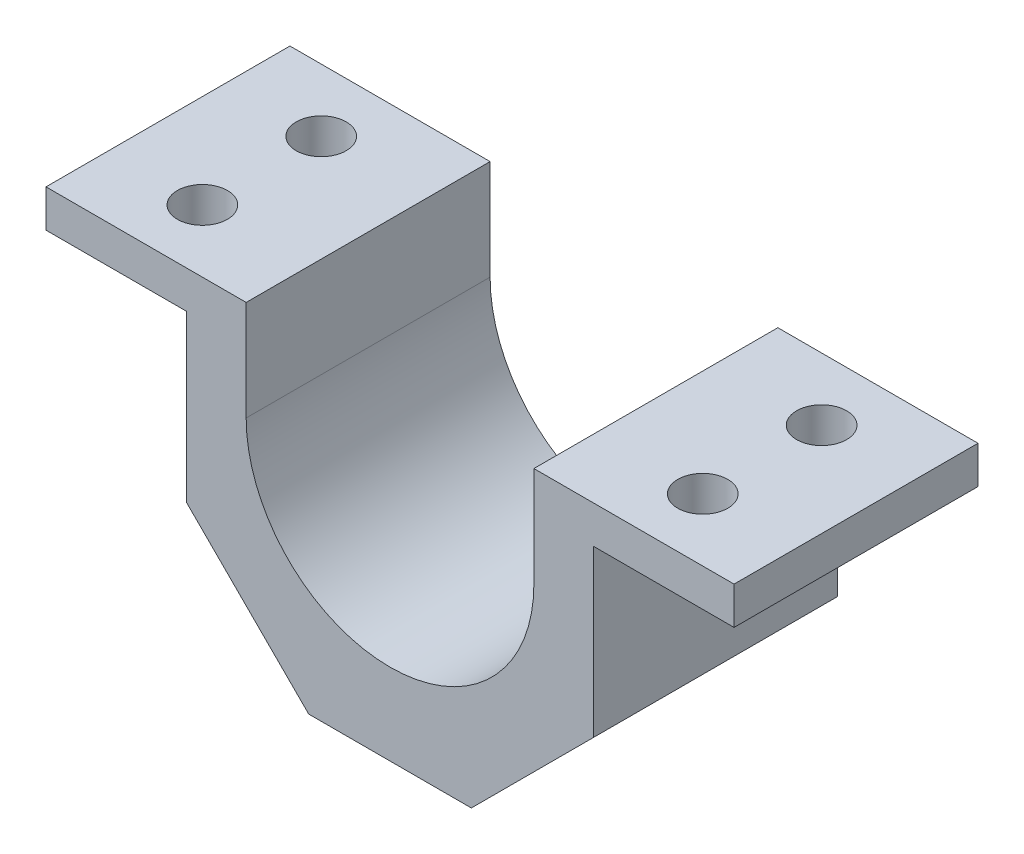
SolidWorks part; units mm, degrees
ref_plane "Front Plane" through (0, 0, 0) normal (0, 0, 1) x (1, 0, 0)
ref_plane "Top Plane" through (0, 0, 0) normal (0, 1, 0) x (1, 0, 0)
ref_plane "Right Plane" through (0, 0, 0) normal (1, 0, 0) x (0, 0, -1)
sketch "Sketch1" plane through (0, 0, 0) normal (0, 0, 1) x (1, 0, 0)
  line L0 (-55, 16) -> (-23, 16)
  line L1 (-23, 16) -> (-23, 0)
  line L2 (-55, 16) -> (-55, 10)
  line L3 (-55, 10) -> (-32.5, 10)
  line L4 (-32.5, 10) -> (-32.5, -36)
  line L5 (-32.5, -36) -> (32.5, -36)
  line L6 (32.5, -36) -> (32.5, 10)
  line L7 (32.5, 10) -> (55, 10)
  line L8 (55, 10) -> (55, 16)
  line L9 (55, 16) -> (23, 16)
  line L10 (23, 16) -> (23, 0)
  line L11 (0, 16.7921) -> (0, -7.6727) construction
  line L12 (32.5, -16.5) -> (13, -36)
  line L13 (-32.5, -16.5) -> (-13, -36)
  arc A0 (-23, 0) -> (23, 0) centre (0, 0) ccw
  point P18 (-55, 13)
  dimension "D1" = 23
  dimension "D2" = 65
  dimension "D3" = 16
  dimension "D4" = 6
  dimension "D5" = 52
  dimension "D6" = 110
  dimension "D7" = 45
  dimension "D8" = 13
extrude "Boss-Extrude2" add sketch "Sketch1" along normal mid plane 39 contours A0 L1 L0 L2 L3 L4 L13 L5 L12 L6 L7 L8 L9 L10
sketch "Sketch3" plane through (0, 16, 0) normal (0, 1, 0) x (1, 0, 0)
  line L0 (-4.1699, 0) -> (13.4992, 0) construction
  line L1 (0, 6.9263) -> (0, -6.3609) construction
  circle A0 centre (40, 9.5) radius 4
  circle A1 centre (-40, 9.5) radius 4
  circle A2 centre (40, -9.5) radius 4
  circle A3 centre (-40, -9.5) radius 4
  dimension "D1" = 8
  dimension "D2" = 40
  dimension "D3" = 9.5
extrude "Cut-Extrude2" cut sketch "Sketch3" against normal blind 20
